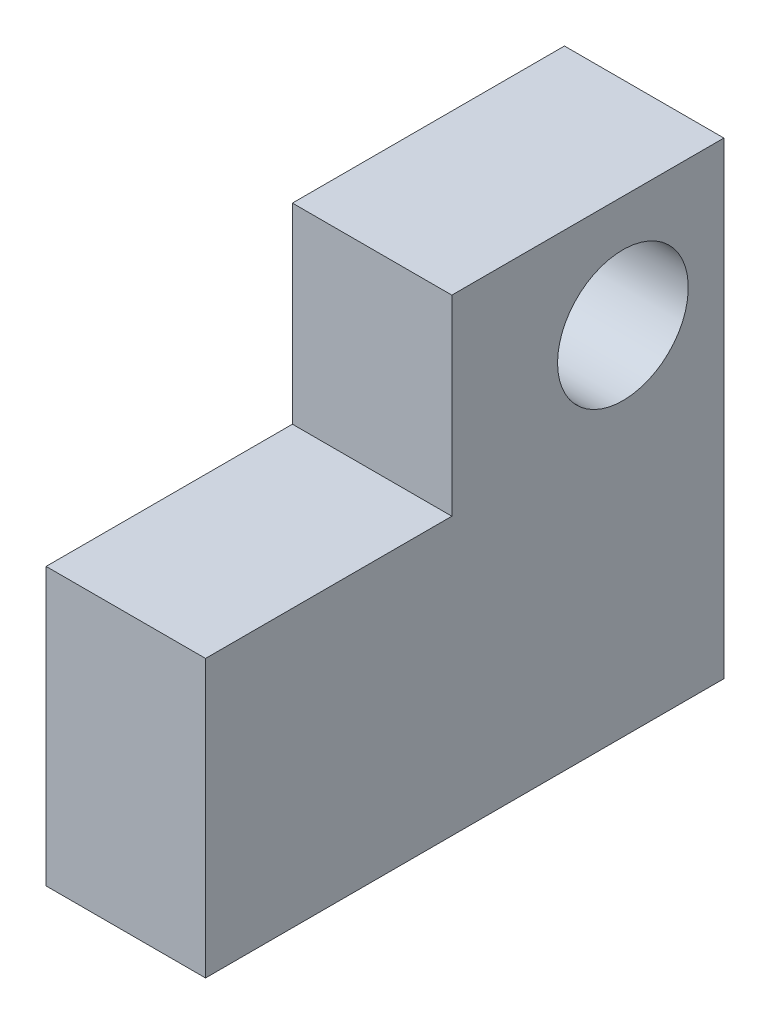
SolidWorks part; units mm, degrees
ref_plane "Front Plane" through (0, 0, 0) normal (0, 0, 1) x (1, 0, 0)
ref_plane "Top Plane" through (0, 0, 0) normal (0, 1, 0) x (1, 0, 0)
ref_plane "Right Plane" through (0, 0, 0) normal (1, 0, 0) x (0, 0, -1)
sketch "Sketch1" plane through (0, 0, 0) normal (0, 0, 1) x (1, 0, 0)
  line L0 (-37.9035, 31.8856) -> (4.5965, 31.8856)
  line L1 (-37.9035, 31.8856) -> (-37.9035, -23.9644)
  line L2 (-37.9035, -23.9644) -> (4.5965, -23.9644)
  line L3 (4.5965, -23.9644) -> (4.5965, 31.8856)
  dimension "D1" = 42.5
  dimension "D2" = 55.85
extrude "Boss-Extrude2" add sketch "Sketch1" along normal blind 42.5
sketch "Sketch5" plane through (0, 0, 42.5) normal (0, 0, 1) x (1, 0, 0)
  line L0 (-31.9035, 31.8856) -> (-31.9035, 20.046) construction
  line L1 (4.5965, 31.8856) -> (-37.9035, 31.8856) construction
  line L2 (-37.9035, 25.8856) -> (-26.7205, 25.8856) construction
  line L3 (-37.9035, 31.8856) -> (-37.9035, -23.9644) construction
  line L4 (-16.6535, 31.8856) -> (-16.6535, 20.4837) construction
  circle A0 centre (-31.9035, 25.9658) radius 3
  circle A1 centre (-1.4035, 25.9658) radius 3
  dimension "D1" = 6
  dimension "D2" = 6
extrude "Cut-Extrude2" cut sketch "Sketch5" against normal blind 42.5
sketch "Sketch6" plane through (-37.9035, 0, 0) normal (-1, 0, 0) x (0, 0, 1)
  line L0 (21.25, 22.9658) -> (21.25, -23.9644) construction
  line L1 (0, 22.9658) -> (42.5, 22.9658) construction
  line L2 (42.5, -23.9644) -> (0, -23.9644) construction
  line L3 (21.25, -0.4993) -> (0, -0.4993) construction
  line L4 (0, 31.8856) -> (0, -23.9644) construction
  line L5 (0, 20.7507) -> (42.5, 20.7507)
  line L6 (42.5, 31.8856) -> (42.5, -23.9644) construction
  line L7 (42.5, 20.7507) -> (42.5, -21.7493)
  line L8 (42.5, -21.7493) -> (0, -21.7493)
  line L9 (0, -21.7493) -> (0, 20.7507)
  dimension "D1" = 42.5
extrude "Cut-Extrude3" cut sketch "Sketch6" against normal blind 39.5
sketch "Sketch7" plane through (4.5965, 0, 0) normal (1, 0, 0) x (0, 0, -1)
  line L0 (-21.25, -21.7493) -> (-21.25, 20.7507) construction
  line L1 (0, -21.7493) -> (-42.5, -21.7493) construction
  line L2 (-42.5, 20.7507) -> (0, 20.7507) construction
  line L3 (-42.5, 20.7507) -> (0, 20.7507) construction
  line L4 (-42.5, -23.9644) -> (-42.5, 31.8856) construction
  line L5 (-42.5, -0.4993) -> (0, -0.4993) construction
  line L6 (0, 20.7507) -> (0, -21.7493) construction
  line L7 (0, -21.7493) -> (-42.5, -21.7493) construction
  line L8 (-42.5, -21.7493) -> (-42.5, 20.7507) construction
  line L9 (-42.5, -16.2493) -> (0, -16.2493) construction
  line L10 (-37, 20.7507) -> (-37, -21.7493) construction
  line L11 (-42.5, 14.7507) -> (0, 14.7507) construction
  circle A0 centre (-21.25, -0.4993) radius 12
  circle A1 centre (-37, -16.2493) radius 1.5
  circle A2 centre (-5.5, -16.2493) radius 1.5
  circle A3 centre (-37, 14.7507) radius 1.5
  circle A4 centre (-5.5, 14.7507) radius 1.5
  dimension "D1" = 5.5
  dimension "D3" = 31
  dimension "D2" = 5.5
  dimension "D4" = 6
extrude "Cut-Extrude4" cut sketch "Sketch7" against normal blind 39.5
sketch "Sketch9" plane through (0, -23.9644, 0) normal (0, -1, 0) x (1, 0, 0)
  line L0 (-37.9035, 42.5) -> (-27.9035, 42.5)
  line L1 (-37.9035, 42.5) -> (4.5965, 42.5) construction
  line L2 (-27.9035, 42.5) -> (-27.9035, 0)
  line L3 (-37.9035, 0) -> (4.5965, 0) construction
  line L4 (-27.9035, 0) -> (-37.9035, 0)
  line L5 (-37.9035, 0) -> (-37.9035, 42.5)
extrude "Cut-Extrude5" cut sketch "Sketch9" against normal blind 39.5
chamfer "Chamfer1" distance 3 angle 45 2 edges at (-37.9035, 31.8856, 21.25) (-37.9035, 20.7507, 21.25)
chamfer "Chamfer2" distance 2 angle 45 1 edges at (4.5965, -23.9644, 21.25)
sketch "Sketch10" plane through (-27.9035, 0, 0) normal (-1, 0, 0) x (0, 0, 1)
  line L1 (42.5, -23.9644) -> (44.5, -23.9644)
  line L4 (42.5, -21.7493) -> (44.5, -21.7493)
  line L5 (44.5, -21.7493) -> (44.5, -23.9644)
  line L7 (42.5, -21.7493) -> (42.5, -23.9644)
  line L8 (21.25, -21.7493) -> (21.25, -23.9644) construction
  line L9 (0, -21.7493) -> (42.5, -21.7493) construction
  line L10 (0, -23.9644) -> (42.5, -23.9644) construction
  line L11 (0, -21.7493) -> (-2, -21.7493)
  line L12 (-2, -21.7493) -> (-2, -23.9644)
  line L13 (0, -23.9644) -> (-2, -23.9644)
  line L14 (0, -21.7493) -> (0, -23.9644)
  dimension "D1" = 2
extrude "Boss-Extrude3" add sketch "Sketch10" against normal blind 3
sketch "Sketch12" plane through (1.5965, 0, 0) normal (-1, 0, 0) x (0, 0, 1)
  line L0 (42.5, 20.7507) -> (42.5, 17.7507)
  line L1 (42.5, -21.7493) -> (42.5, 20.7507) construction
  line L2 (42.5, 17.7507) -> (44.5, 17.7507)
  line L3 (44.5, 17.7507) -> (44.5, 20.7507)
  line L4 (44.5, 20.7507) -> (42.5, 20.7507)
  line L5 (21.25, 20.7507) -> (21.25, -21.7493) construction
  line L6 (42.5, 20.7507) -> (0, 20.7507) construction
  line L7 (-2, -21.7493) -> (44.5, -21.7493) construction
  line L8 (-2, 17.7507) -> (-2, 20.7507)
  line L9 (0, 17.7507) -> (-2, 17.7507)
  line L10 (0, 20.7507) -> (0, 17.7507)
  line L11 (-2, 20.7507) -> (0, 20.7507)
  dimension "D1" = 3
extrude "Boss-Extrude4" add sketch "Sketch12" against normal blind 3
sketch "Sketch13" plane through (0, 0, -2) normal (0, 0, -1) x (-1, 0, 0)
  line L0 (-1.5965, 17.7507) -> (24.9035, -21.7493)
  line L1 (-1.5965, 20.7507) -> (27.9035, -21.7493)
  line L2 (27.9035, -21.7493) -> (24.9035, -21.7493)
  line L3 (-1.5965, 20.7507) -> (-1.5965, 17.7507)
extrude "Boss-Extrude5" add sketch "Sketch13" against normal blind 2
sketch "Sketch14" plane through (0, 0, 44.5) normal (0, 0, 1) x (1, 0, 0)
  line L0 (1.5965, 17.7507) -> (-24.9035, -21.7493)
  line L1 (-24.9035, -21.7493) -> (-27.9035, -21.7493)
  line L2 (-27.9035, -21.7493) -> (1.5965, 20.7507)
  line L3 (1.5965, 20.7507) -> (1.5965, 17.7507)
extrude "Boss-Extrude6" add sketch "Sketch14" against normal blind 2
sketch "Sketch16" plane through (4.5965, 0, 0) normal (1, 0, 0) x (0, 0, -1)
  line L0 (-42.5, 30.0689) -> (-33.5, 30.0689)
  line L2 (-42.5, 20.7507) -> (-42.5, 31.8856) construction
  line L3 (-33.5, 30.0689) -> (-33.5, 39.0689)
  line L4 (-33.5, 39.0689) -> (-42.5, 39.0689)
  line L5 (-42.5, 39.0689) -> (-42.5, 30.0689)
  line L6 (-21.25, 31.8856) -> (-21.25, 36.9569) construction
  line L7 (-42.5, 31.8856) -> (0, 31.8856) construction
  line L8 (-9, 39.0689) -> (0, 39.0689)
  line L9 (-9, 30.0689) -> (-9, 39.0689)
  line L10 (0, 30.0689) -> (-9, 30.0689)
  line L11 (0, 39.0689) -> (0, 30.0689)
  line L12 (-38, 39.0689) -> (-38, 30.0689) construction
  line L13 (-42.5, 34.5689) -> (-33.5, 34.5689) construction
  circle A0 centre (-38, 34.5689) radius 3.175
  circle A1 centre (-4.5, 34.5689) radius 3.175
  dimension "D4" = 6.35
  dimension "D1" = 9
  dimension "D2" = 9
extrude "Boss-Extrude8" add sketch "Sketch16" against normal blind 5
sketch "Sketch17" plane through (4.5965, 0, 0) normal (1, 0, 0) x (0, 0, -1)
  circle A0 centre (-38, 34.5689) radius 3
  circle A1 centre (-4.5, 34.5689) radius 3
extrude "Cut-Extrude6" cut sketch "Sketch17" against normal blind 5
sketch "Sketch18" plane through (-0.4035, 0, 0) normal (-1, 0, 0) x (0, 0, 1)
  line L0 (0, 39.0689) -> (9, 39.0689)
  line L1 (9, 39.0689) -> (9, 31.8856)
  line L2 (9, 31.8856) -> (0, 31.8856)
  line L3 (0, 31.8856) -> (0, 39.0689)
  line L4 (21.25, 39.3131) -> (21.25, 31.8856) construction
  line L5 (0, 31.8856) -> (42.5, 31.8856) construction
  line L6 (33.5, 31.8856) -> (42.5, 31.8856)
  line L7 (33.5, 39.0689) -> (33.5, 31.8856)
  line L8 (42.5, 39.0689) -> (33.5, 39.0689)
  line L9 (42.5, 31.8856) -> (42.5, 39.0689)
extrude "Boss-Extrude9" add sketch "Sketch18" along normal blind 2
sketch "Sketch19" plane through (4.5965, 0, 0) normal (1, 0, 0) x (0, 0, -1)
  line L0 (-21.25, 31.8856) -> (-21.25, 35.0374) construction
  line L1 (-33.5, 31.8856) -> (-9, 31.8856) construction
  circle A0 centre (-38, 34.5689) radius 3.175
  circle A1 centre (-4.5, 34.5689) radius 3.175
  dimension "D1" = 6.35
  dimension "D2" = 6.35
extrude "Cut-Extrude7" cut sketch "Sketch19" against normal blind 5
sketch "Sketch20" plane through (0, 0, 42.5) normal (0, 0, 1) x (1, 0, 0)
  line L0 (-34.9035, 20.7507) -> (1.5965, 20.7507)
  line L1 (1.5965, 20.7507) -> (1.5965, -24.5984)
  line L2 (1.5965, -24.5984) -> (-34.9035, -24.5984)
  line L3 (-34.9035, -24.5984) -> (-34.9035, 20.7507)
extrude "Cut-Extrude9" cut sketch "Sketch20" against normal mid plane 132
sketch "Sketch21" plane through (4.5965, 0, 0) normal (1, 0, 0) x (0, 0, -1)
  line L0 (0, 39.0689) -> (0, -21.9644)
  line L1 (0, -21.9644) -> (2.4617, -21.9644)
  line L2 (2.4617, -21.9644) -> (3.038, 39.0689)
  line L3 (3.038, 39.0689) -> (0.568, 39.0689)
  line L4 (0, 39.0689) -> (0.568, 39.0689)
  line L5 (-21.25, -21.9644) -> (-21.25, 31.8856) construction
  line L6 (-42.5, -21.9644) -> (0, -21.9644) construction
  line L7 (-33.5, 31.8856) -> (-9, 31.8856) construction
  line L8 (-42.5, 39.0689) -> (-42.5, -21.9644)
  line L9 (-42.5, -21.9644) -> (-44.9617, -21.9644)
  line L10 (-44.9617, -21.9644) -> (-45.538, 39.0689)
  line L11 (-45.538, 39.0689) -> (-43.068, 39.0689)
  line L12 (-42.5, 39.0689) -> (-43.068, 39.0689)
extrude "Cut-Extrude10" cut sketch "Sketch21" against normal mid plane 132
sketch "Sketch22" plane through (4.5965, 0, 0) normal (1, 0, 0) x (0, 0, -1)
  circle A0 centre (-21.25, -0.4993) radius 11.45
  circle A1 centre (-21.25, -0.4993) radius 12
  circle A2 centre (-37, 14.7507) radius 1.5
  circle A3 centre (-5.5246, 14.7507) radius 1.55
  circle A4 centre (-5.5, -16.2493) radius 1.5
  circle A5 centre (-37, -16.2493) radius 1.5
  dimension "D1" = 22.9
extrude "Boss-Extrude13" add sketch "Sketch22" against normal blind 3
sketch "Sketch23" plane through (4.5965, 0, 0) normal (1, 0, 0) x (0, 0, -1)
  line L0 (-42.5, -16.4993) -> (0, -16.4993)
  line L1 (-42.5, -21.9644) -> (-42.5, 39.0689) construction
  line L2 (0, -21.9644) -> (0, 39.0689) construction
  line L3 (0, -16.4993) -> (0, -23.9644)
  line L4 (0, -23.9644) -> (-42.5, -23.9644)
  line L5 (-42.5, -23.9644) -> (-42.5, -21.9644) construction
  line L6 (0, -23.9644) -> (-42.5, -23.9644) construction
  line L7 (-42.5, -23.9644) -> (-42.5, -16.4993)
  circle A0 centre (-21.25, -0.4993) radius 11.45 construction
  dimension "D1" = 16
extrude "Cut-Extrude11" cut sketch "Sketch23" against normal blind 3
chamfer "Chamfer3" distance 2 angle 45 1 edges at (4.5965, -16.4993, 21.25)
sketch "Sketch24" plane through (1.5965, 0, 0) normal (-1, 0, 0) x (0, 0, 1)
  circle A0 centre (21.25, -0.4993) radius 11.45
  circle A1 centre (21.25, -0.4993) radius 13.75
  dimension "D1" = 27.5
extrude "Boss-Extrude14" add sketch "Sketch24" along normal blind 4
sketch "Sketch25" plane through (4.5965, 0, 0) normal (1, 0, 0) x (0, 0, -1)
  line L0 (-32.7, -0.4993) -> (-9.8, -0.4993) construction
  line L1 (-30.9649, 5.5607) -> (-11.5351, 5.5607) construction
  line L2 (-42.5, 39.0689) -> (-42.5, 5.5607)
  line L3 (-42.5, -14.4993) -> (-42.5, 39.0689) construction
  line L4 (-42.5, 5.5607) -> (0, 5.5607)
  line L5 (0, -14.4993) -> (0, 39.0689) construction
  line L6 (0, 5.5607) -> (0, 39.0689)
  line L7 (0, 39.0689) -> (-42.5, 39.0689)
  circle A0 centre (-21.25, -0.4993) radius 11.45 construction
  circle A1 centre (-38, 34.5689) radius 3.175
  circle A2 centre (-4.5, 34.5689) radius 3.175
  dimension "D2" = 6.35
  dimension "D3" = 6.35
  dimension "D1" = 6.06
extrude "Boss-Extrude15" add sketch "Sketch25" along normal blind 10
sketch "Sketch26" plane through (0, 0, 0) normal (0, 0, -1) x (-1, 0, 0)
  line L0 (-4.5965, 39.0689) -> (-4.5965, -17.8566)
  line L1 (-4.5965, -17.8566) -> (37.4199, -17.8566)
  line L2 (37.4199, -17.8566) -> (42.5732, 39.0689)
  line L3 (42.5732, 39.0689) -> (-4.5965, 39.0689)
extrude "Cut-Extrude12" cut sketch "Sketch26" against normal blind 142
chamfer "Chamfer4" distance 10 angle 45 2 edges at (9.5965, 5.5607, 0) (9.5965, 5.5607, 42.5)
sketch "Sketch27" plane through (0, 5.5607, 0) normal (0, -1, 0) x (1, 0, 0)
  line L0 (9.5965, 32.5) -> (9.5965, 10) construction
  line L1 (14.5965, 32.5) -> (4.5965, 32.5) construction
  line L2 (4.5965, 10) -> (14.5965, 10) construction
  line L3 (11.0398, 21.25) -> (11.0398, 22.277)
  line L4 (11.0398, 22.277) -> (12.8717, 22.277)
  line L5 (12.8717, 22.277) -> (12.8717, 21.25)
  line L6 (12.8717, 21.25) -> (11.0398, 21.25)
extrude "Boss-Extrude16" add sketch "Sketch27" along normal blind 0.2
sketch "Sketch28" plane through (14.5965, 0, 0) normal (1, 0, 0) x (0, 0, -1)
  line L0 (-42.5789, 40.0689) -> (0, 40.0689)
  line L1 (0, 39.0689) -> (-42.5, 39.0689) construction
  line L2 (-42.5789, 40.0689) -> (-43.5, 40.0689)
  line L3 (-43.5, 40.0689) -> (-43.5, 15.1465)
  line L4 (-43.5, 15.1465) -> (-33.8642, 5.5107)
  line L5 (-33.8642, 5.5107) -> (-8.6358, 5.5107)
  line L6 (-8.6358, 5.5107) -> (1, 15.1465)
  line L7 (1, 15.1465) -> (1, 40.0689)
  line L8 (1, 40.0689) -> (0, 40.0689)
  line L9 (-42.5, 39.0689) -> (-42.5, 15.5607) construction
  line L10 (0, 15.5607) -> (0, 39.0689) construction
  line L11 (-10, 5.5607) -> (0, 15.5607) construction
  line L12 (-42.5, 15.5607) -> (-32.5, 5.5607) construction
  line L13 (-32.5, 5.5607) -> (-10, 5.5607) construction
  circle A0 centre (-38, 34.5689) radius 3.175
  circle A1 centre (-4.5, 34.5689) radius 3.175
  dimension "D1" = 1
  dimension "D2" = 1
  dimension "D3" = 1
  dimension "D4" = 1
  dimension "D5" = 1
  dimension "D6" = 0.05
extrude "Boss-Extrude17" add sketch "Sketch28" against normal blind 10
sketch "Sketch29" plane through (4.5965, 0, 0) normal (-1, 0, 0) x (0, 0, 1)
  line L0 (-5, 45.0689) -> (-5, 1.0107)
  line L2 (43.7723, 1.0107) -> (43.7723, 27.0511)
  line L3 (43.7723, 27.0511) -> (20.5972, 27.0511)
  line L4 (20.5972, 27.0511) -> (20.5972, 45.0689)
  line L5 (20.5972, 45.0689) -> (-5, 45.0689)
  line L6 (-5, 1.0107) -> (43.7723, 1.0107)
  line L7 (33.8642, 5.5107) -> (8.6358, 5.5107) construction
  line L8 (-1, 40.0689) -> (43.5, 40.0689) construction
  line L9 (-1, 15.1465) -> (-1, 40.0689) construction
  circle A0 centre (4.5, 34.5689) radius 6.15
  dimension "D4" = 12.3
  dimension "D1" = 4.5
  dimension "D2" = 5
  dimension "D3" = 4
extrude "Boss-Extrude19" add sketch "Sketch29" along normal blind 15
sketch "Sketch30" plane through (0, 0, 43.7723) normal (0, 0, 1) x (1, 0, 0)
  line L0 (4.5965, 40.0689) -> (4.5965, 5.5107)
  line L1 (4.5965, 5.5107) -> (14.5965, 4.3657)
  line L2 (14.5965, 4.3657) -> (14.5965, 40.0689)
  line L3 (14.5965, 40.0689) -> (4.5965, 40.0689)
extrude "Cut-Extrude13" cut sketch "Sketch30" against normal blind 50
